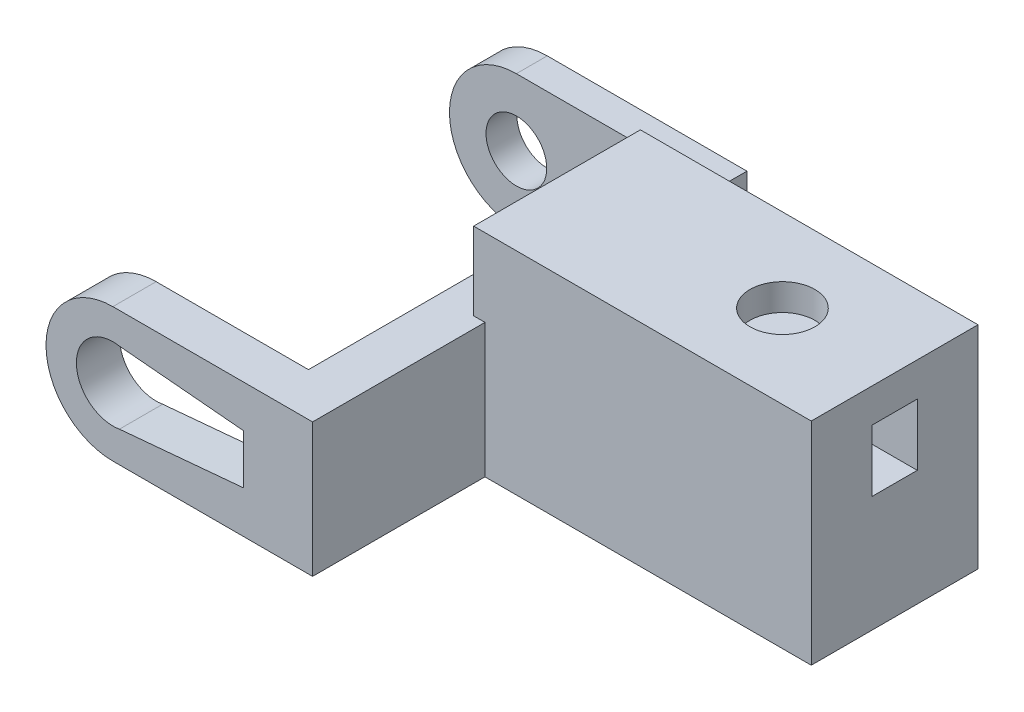
SolidWorks part; units mm, degrees
material "ABS"
ref_plane "Front Plane" through (0, 0, 0) normal (0, 0, 1) x (1, 0, 0)
ref_plane "Top Plane" through (0, 0, 0) normal (0, 1, 0) x (1, 0, 0)
ref_plane "Right Plane" through (0, 0, 0) normal (1, 0, 0) x (0, 0, -1)
sketch "Sketch1" plane through (0, 0, 0) normal (0, 1, 0) x (1, 0, 0)
  line L1 (-41.1, -8.1) -> (-8.3, -8.1)
  line L2 (-41.1, -8.1) -> (-41.1, 8.1)
  line L3 (-41.1, 8.1) -> (-8.3, 8.1)
  line L4 (-8.3, -8.1) -> (-8.3, 8.1)
extrude "Boss-Extrude1" add sketch "Sketch1" along normal mid plane 20.55 from offset 60.725
sketch "Sketch2" plane through (0, 0, 0) normal (1, 0, 0) x (0, 0, -1)
  line L1 (-24.85, -71) -> (17.35, -71)
  line L2 (-24.85, -71) -> (-24.85, -58)
  line L3 (-24.85, -58) -> (17.35, -58)
  line L4 (17.35, -71) -> (17.35, -58)
extrude "Boss-Extrude2" add sketch "Sketch2" along normal mid plane 4.6 from offset 42.3
sketch "Sketch3" plane through (0, 0, 0) normal (0, 0, 1) x (1, 0, 0)
  circle A0 centre (-59.4, -64.5) radius 6.5
extrude "Boss-Extrude3" add sketch "Sketch3" along normal mid plane 4.2 from offset 22.75
sketch "Sketch4" plane through (0, 0, 0) normal (0, 0, 1) x (1, 0, 0)
  line L1 (-59.4, -71) -> (-41.1, -71)
  line L2 (-59.4, -71) -> (-59.4, -58)
  line L3 (-59.4, -58) -> (-41.1, -58)
  line L4 (-41.1, -71) -> (-41.1, -58)
  circle A0 centre (-59.4, -64.5) radius 6.5 construction
extrude "Boss-Extrude4" add sketch "Sketch4" along normal mid plane 4.2 from offset 22.75
sketch "Sketch5" plane through (0, 0, 0) normal (0, 0, 1) x (1, 0, 0)
  circle A0 centre (-59.4, -64.5) radius 3.55
extrude "Cut-Extrude1" cut sketch "Sketch5" against normal mid plane 4.2 from offset 22.75
sketch "Sketch6" plane through (0, 0, 0) normal (0, 0, 1) x (1, 0, 0)
  line L0 (-59.4, -60.95) -> (-46.7, -62.0967)
  line L1 (-46.7, -62.0967) -> (-46.7, -66.9033)
  line L2 (-46.7, -66.9033) -> (-59.4, -68.05)
  line L3 (-59.4, -68.05) -> (-59.4, -60.95)
  circle A0 centre (-59.4, -64.5) radius 3.55 construction
extrude "Cut-Extrude2" cut sketch "Sketch6" against normal mid plane 4.2 from offset 22.75
sketch "Sketch7" plane through (0, 0, 0) normal (0, 0, 1) x (1, 0, 0)
  circle A0 centre (-59.4, -64.5) radius 6.5
extrude "Boss-Extrude5" add sketch "Sketch7" along normal mid plane 3 from offset 15.85
sketch "Sketch8" plane through (0, 0, 0) normal (0, 0, 1) x (1, 0, 0)
  line L1 (-59.4, -71) -> (-41.1, -71)
  line L2 (-59.4, -71) -> (-59.4, -58)
  line L3 (-59.4, -58) -> (-41.1, -58)
  line L4 (-41.1, -71) -> (-41.1, -58)
extrude "Boss-Extrude6" add sketch "Sketch8" along normal mid plane 3 from offset 15.85
sketch "Sketch9" plane through (0, 0, 0) normal (0, 0, 1) x (1, 0, 0)
  circle A0 centre (-59.4, -64.5) radius 2.95
extrude "Cut-Extrude3" cut sketch "Sketch9" against normal mid plane 3 from offset 15.85
sketch "Sketch10" plane through (0, 0, 0) normal (0, 1, 0) x (1, 0, 0)
  line L1 (-36.3, -6.5) -> (-13.1, -6.5)
  line L2 (-36.3, -6.5) -> (-36.3, 6.5)
  line L3 (-36.3, 6.5) -> (-13.1, 6.5)
  line L4 (-13.1, -6.5) -> (-13.1, 6.5)
extrude "Cut-Extrude4" cut sketch "Sketch10" against normal mid plane 17.25 from offset 62.375
sketch "Sketch11" plane through (0, 0, 0) normal (0, 1, 0) x (1, 0, 0)
  circle A0 centre (-38.45, 0) radius 1
extrude "Cut-Extrude5" cut sketch "Sketch11" against normal mid plane 6 from offset 68
sketch "Sketch12" plane through (0, 0, 0) normal (0, 1, 0) x (1, 0, 0)
  circle A0 centre (-10.95, 0) radius 1
extrude "Cut-Extrude6" cut sketch "Sketch12" against normal mid plane 6 from offset 68
sketch "Sketch13" plane through (0, 0, 0) normal (0, 1, 0) x (1, 0, 0)
  circle A0 centre (-19.2, 0) radius 3.15
extrude "Cut-Extrude7" cut sketch "Sketch13" against normal mid plane 2.6 from offset 51.75
sketch "Sketch14" plane through (0, 0, 0) normal (1, 0, 0) x (0, 0, -1)
  line L1 (-2.2, -59.75) -> (2.2, -59.75)
  line L2 (-2.2, -59.75) -> (-2.2, -53.75)
  line L3 (-2.2, -53.75) -> (2.2, -53.75)
  line L4 (2.2, -59.75) -> (2.2, -53.75)
extrude "Cut-Extrude8" cut sketch "Sketch14" against normal mid plane 4.8 from offset 10.7
